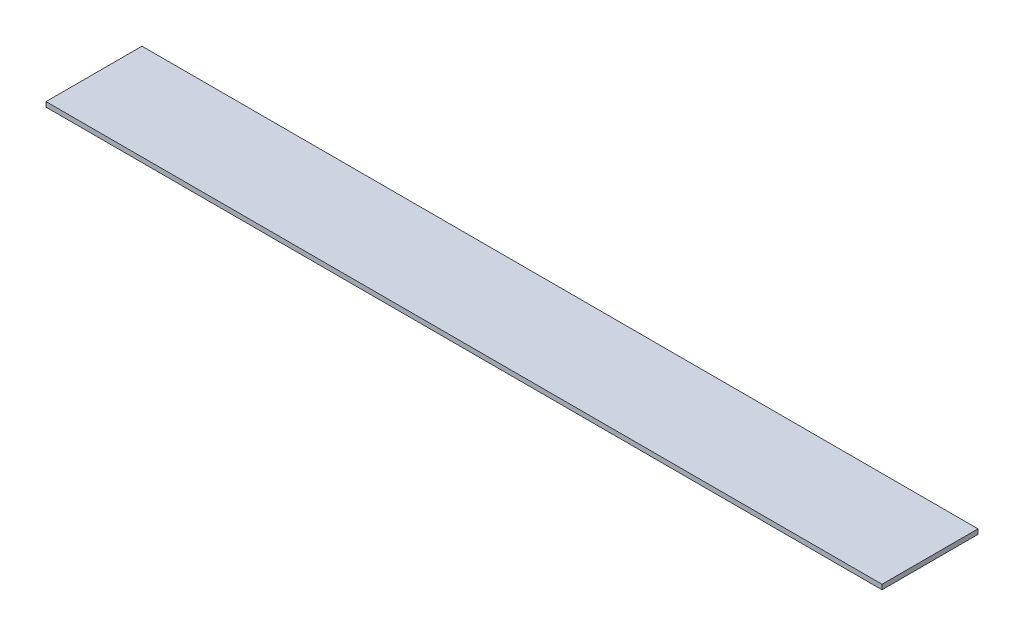
SolidWorks part; units mm, degrees
ref_plane "Front Plane" through (0, 0, 0) normal (0, 0, 1) x (1, 0, 0)
ref_plane "Top Plane" through (0, 0, 0) normal (0, 1, 0) x (1, 0, 0)
ref_plane "Right Plane" through (0, 0, 0) normal (1, 0, 0) x (0, 0, -1)
sketch "Sketch1" plane through (0, 0, 0) normal (1, 0, 0) x (0, 0, -1)
  line L1 (25, -1.2586) -> (-25, -1.2586)
  line L2 (25, -1.2586) -> (25, 1.2586)
  line L3 (25, 1.2586) -> (-25, 1.2586)
  line L4 (-25, -1.2586) -> (-25, 1.2586)
  line L5 (25, -1.2586) -> (-25, 1.2586) construction
  line L6 (25, 1.2586) -> (-25, -1.2586) construction
  line L7 (28.5895, -3.8405) -> (-28.5895, -3.8405)
  line L8 (28.5895, -3.8405) -> (28.5895, 3.8405)
  line L9 (28.5895, 3.8405) -> (-28.5895, 3.8405)
  line L10 (-28.5895, -3.8405) -> (-28.5895, 3.8405)
  line L11 (28.5895, -3.8405) -> (-28.5895, 3.8405) construction
  line L12 (28.5895, 3.8405) -> (-28.5895, -3.8405) construction
  point P0 (0, 0)
  point P6 (0, 0)
  dimension "D1" = 50
  dimension "D2" = 2.5171
  dimension "D3" = 7.681
extrude "Boss-Extrude1" add sketch "Sketch1" along normal blind 435.4951 contours L4 L1 L2 L3
